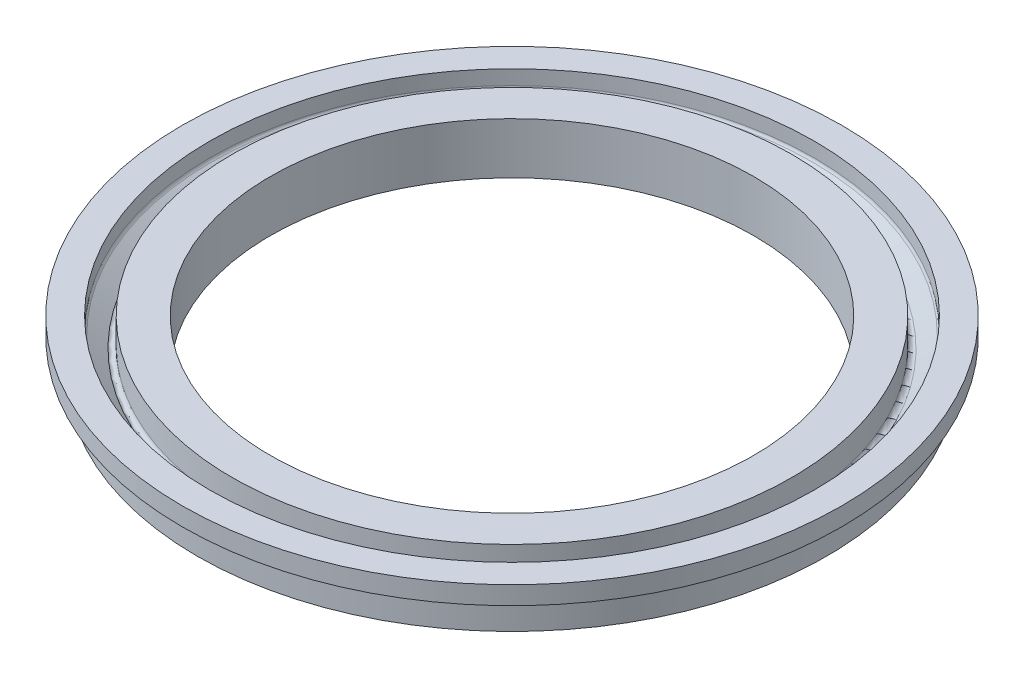
SolidWorks part; units mm, degrees
ref_plane "Front Plane" through (0, 0, 0) normal (0, 0, 1) x (1, 0, 0)
ref_plane "Top Plane" through (0, 0, 0) normal (0, 1, 0) x (1, 0, 0)
ref_plane "Right Plane" through (0, 0, 0) normal (1, 0, 0) x (0, 0, -1)
sketch "Sketch1" plane through (0, 0, 0) normal (0, 0, 1) x (1, 0, 0)
  line L9 (0, -2.5296) -> (0, 7.7324) construction
  line L26 (-16.5, 0.0455) -> (-16.5, 3.5455)
  line L51 (-22.5091, 2.3276) -> (-22.5091, 3.5687)
  line L52 (-22.5091, 3.5687) -> (-20.6364, 3.5687)
  line L55 (-19.1091, 1.335) -> (-19.1091, 3.5455)
  line L56 (-19.1091, 3.5455) -> (-16.5, 3.5455)
  line L60 (-16.5, 0.0455) -> (-21.4909, 0.083)
  line L61 (-21.4909, 0.083) -> (-21.4909, 1.894)
  line L62 (-21.4909, 1.894) -> (-22.5091, 2.3276)
  line L65 (-20.6364, 3.5687) -> (-20.6364, 2.4441)
  line L66 (-20.6364, 2.4441) -> (-19.1091, 1.335)
  point P0 (-20.6364, 2.4441)
  dimension "D1" = 16.5
  dimension "D3" = 3.5
revolve "Revolución1" add sketch "Sketch1" angle 360 about L9
fillet "Redondeo1" radius 0.25 3 edges at (0, 2.4441, -20.6364) (0, 1.335, -19.1091) (0, 1.894, -21.4909)
